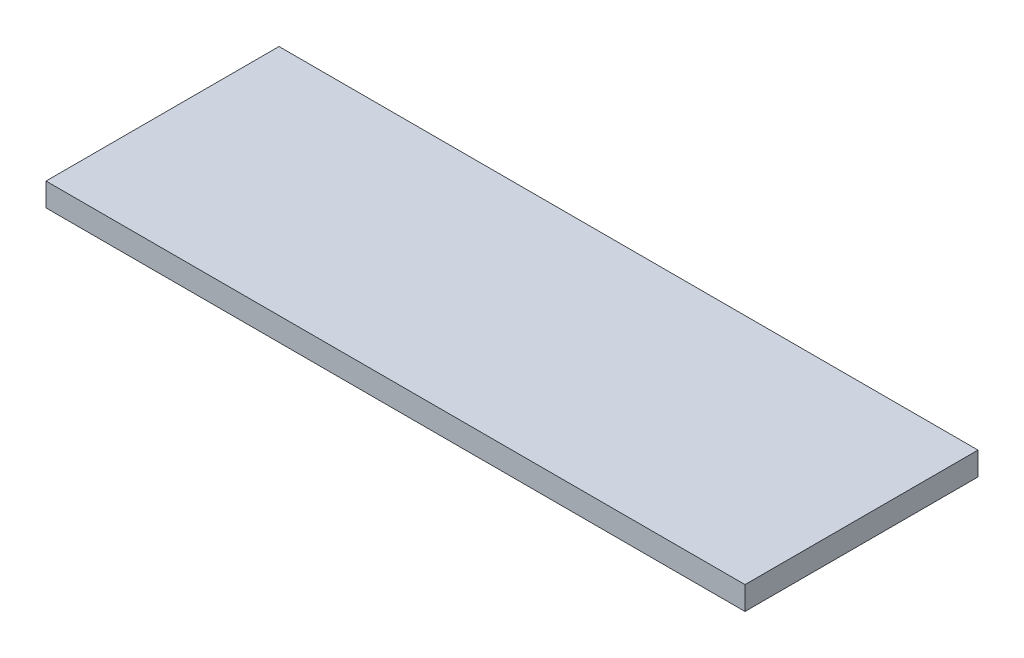
SolidWorks part; units mm, degrees
material "Maple"
ref_plane "Front Plane" through (0, 0, 0) normal (0, 0, 1) x (1, 0, 0)
ref_plane "Top Plane" through (0, 0, 0) normal (0, 1, 0) x (1, 0, 0)
ref_plane "Right Plane" through (0, 0, 0) normal (1, 0, 0) x (0, 0, -1)
sketch "Sketch1" plane through (0, 0, 0) normal (0, 1, 0) x (1, 0, 0)
  line L1 (150, 50) -> (-150, 50)
  line L2 (150, 50) -> (150, -50)
  line L3 (150, -50) -> (-150, -50)
  line L4 (-150, 50) -> (-150, -50)
  line L5 (150, 50) -> (-150, -50) construction
  line L6 (150, -50) -> (-150, 50) construction
  point P0 (0, 0)
  dimension "D1" = 300
  dimension "D2" = 100
extrude "Boss-Extrude1" add sketch "Sketch1" along normal blind 10
